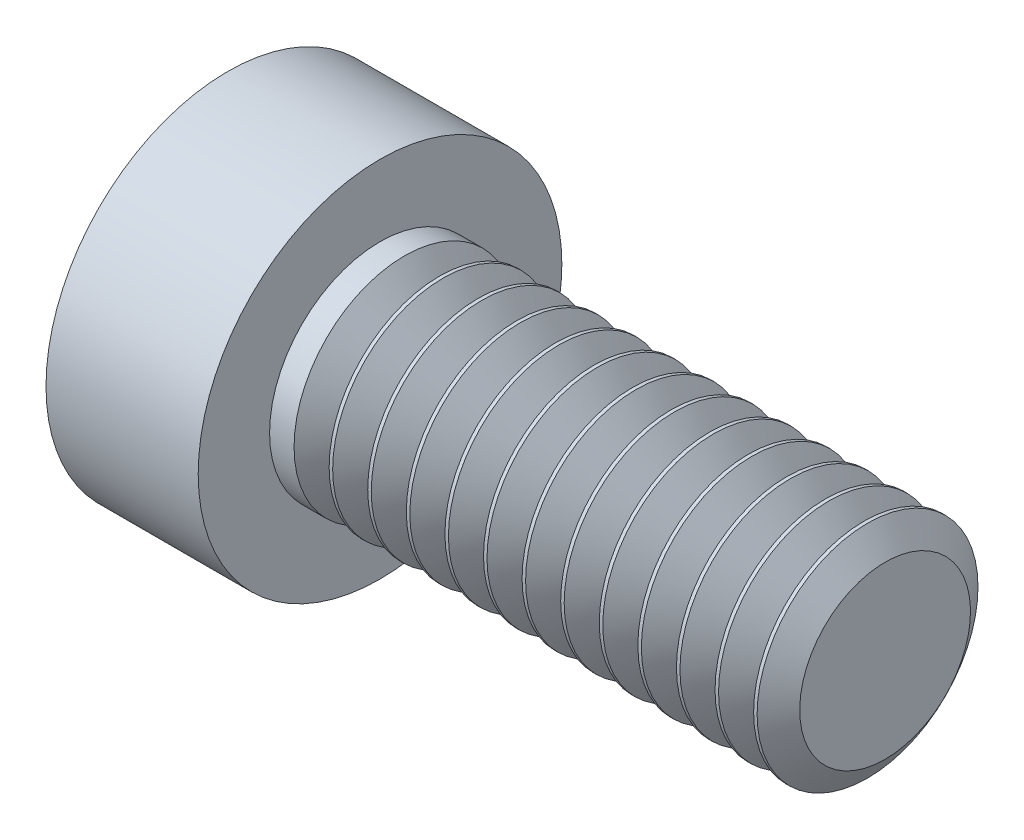
SolidWorks part; units mm, degrees
ref_plane "Plane1" through (0, 0, 0) normal (0, 0, 1) x (1, 0, 0)
ref_plane "Plane2" through (0, 0, 0) normal (0, 1, 0) x (1, 0, 0)
ref_plane "Plane3" through (0, 0, 0) normal (1, 0, 0) x (0, 0, -1)
sketch "BodySke" plane through (0, 0, 0) normal (0, 0, 1) x (1, 0, 0)
  line L0 (3.9624, 2.0828) -> (3.9624, 3.429)
  line L1 (3.9624, 3.429) -> (1.0922, 3.429)
  line L2 (-25.4, 0) -> (127, 0) construction
  line L3 (13.4874, 0) -> (0, 0)
  line L4 (3.9624, 2.0828) -> (13.4874, 2.0828)
  line L5 (13.4874, 2.0828) -> (13.4874, 0)
  line L6 (3.9624, -3.429) -> (1.0922, -3.429) construction
  line L7 (3.9624, -2.0828) -> (13.4874, -2.0828) construction
  line L8 (4.7549, 1.2192) -> (4.7549, -0.4698) construction
  line L9 (3.9624, 1.2192) -> (3.9624, -0.4698) construction
  arc A0 (0, 0) -> (1.0922, 3.429) centre (5.9288, 0) cw
  dimension "Diameter" = 4.1656
  dimension "Head_dia" = 6.858
  dimension "Head_ht" = 3.9624
  dimension "Length" = 9.525
  dimension "Head_side_ht" = 2.8702
  dimension "Thread_nom" = 9.525
  dimension "Advance" = 0.7925
revolve "Base-Revolve" add sketch "BodySke" angle 360 about L2
cosmetic thread "ThreadCosmetic" [suppressed] parameters "Thread_length"=8.7325, "Thread_minor"=3.2207
sketch "Sketch2" plane through (0, 0, 0) normal (1, 0, 0) x (0, 0, -1)
  line L0 (-3.429, -0.6858) -> (-3.429, 0.6858)
  line L1 (-3.429, 0.6858) -> (3.429, 0.6858)
  line L2 (3.429, 0.6858) -> (3.429, -0.6858)
  line L3 (3.429, -0.6858) -> (-3.429, -0.6858)
  dimension "D1" = 6.858
  dimension "D2" = 3.429
  dimension "D3" = 0.6858
  dimension "Slot_width" = 1.3716
extrude "Slot" [suppressed] cut sketch "Sketch2" along normal blind 1.8034
sketch "Sketch3" plane through (0, 0, 0) normal (1, 0, 0) x (0, 0, -1)
  line L0 (0.4953, -2.5654) -> (-0.4953, -2.5654)
  line L1 (0.4953, -2.5654) -> (0.4953, 2.5654)
  line L2 (-0.4953, 2.5654) -> (0.4953, 2.5654)
  line L3 (-0.4953, 2.5654) -> (-0.4953, -2.5654)
  dimension "Cross_width" = 0.9906
  dimension "D1" = 0.4953
  dimension "Cross_dia" = 5.1308
  dimension "D2" = 2.5654
ref_plane "Plane4" through (2.9972, 0, 0) normal (1, 0, 0) x (0, 0, -1)
sketch "Sketch4" plane through (2.9972, 0, 0) normal (1, 0, 0) x (0, 0, -1)
  line L0 (0.2477, -0.2476) -> (-0.2476, -0.2477)
  line L1 (0.2477, -0.2476) -> (0.2477, 0.2476)
  line L2 (-0.2476, 0.2476) -> (0.2477, 0.2476)
  line L3 (-0.2476, 0.2476) -> (-0.2476, -0.2477)
  dimension "D1" = 0.4953
  dimension "D2" = 0.2476
  dimension "D3" = 0.4953
  dimension "D4" = 0.2476
loft "Cross" cut profiles "Sketch3", "Sketch4"
pattern_circular "CirPattern1" count 2 every 90 about axis through (0, 0, 0) along (1, 0, 0) of "Cross"
sketch "Sketch5" plane through (0, 0, 0) normal (0, 1, 0) x (1, 0, 0)
  line L4 (-25.4, 0) -> (127, 0) construction
  line L5 (3.9624, -6.312) -> (3.9624, 6.3337) construction
  circle A0 centre (2.8702, 0) radius 0.5842
  dimension "Drilled_hole_dia" = 1.1684
  dimension "D1" = 3.9624
  dimension "Drilled_hole_loc" = 1.0922
extrude "Hole" [suppressed] cut sketch "Sketch5" against normal through all and the other way through all
sketch "ThdSchSke" plane through (0, 0, 0) normal (0, 0, 1) x (1, 0, 0)
  line L0 (4.7549, -1.6104) -> (4.4241, -2.0828)
  line L1 (4.7549, -1.6104) -> (5.0857, -2.0828)
  line L2 (5.0857, -2.0828) -> (5.0857, -2.6035)
  line L3 (-3.175, 0) -> (5.1513, 0) construction
  line L5 (5.0857, -2.6035) -> (4.4241, -2.6035)
  line L6 (4.4241, -2.6035) -> (4.4241, -2.0828)
  dimension "Diameter" = 4.1656
  dimension "SideAngle" = 55
  dimension "VeeAngle" = 70
  dimension "Thread_minor" = 3.2207
  dimension "Overcut" = 5.207
  dimension "Start" = 4.7549
revolve "ThreadSchematic" cut sketch "ThdSchSke" angle 360 about L3
pattern_linear "ThdSchPat" count 13 spacing 0.7277 along (1, 0, 0) of "ThreadSchematic"
equation "\"D1@Sketch3\" = \"Cross_width@Sketch3\" / 2"
equation "\"D2@Sketch3\" = \"Cross_dia@Sketch3\" / 2"
equation "\"D1@Sketch4\" = \"Cross_width@Sketch3\"*.5"
equation "\"D2@Sketch4\" = \"D1@Sketch4\" / 2"
equation "\"D3@Sketch4\" = \"D1@Sketch4\""
equation "\"D4@Sketch4\" = \"D2@Sketch4\""
equation "\"D1@Sketch2\" = \"Head_dia@BodySke\""
equation "\"D2@Sketch2\" = \"D1@Sketch2\" / 2"
equation "\"D3@Sketch2\" = \"Slot_width@Sketch2\" / 2"
equation "\"D1@Sketch5\" = \"Head_ht@BodySke\""
equation "\"Thread_length@ThreadCosmetic\" = ((sgn( (\"Length@BodySke\" - \"Advance@BodySke\" ) - \"Thread_nom@BodySke\" )-1)*( (\"Length@BodySke\" - \"Advance@BodySke\" ) - \"Thread_nom@BodySke\" ))/-2+ \"Thread_nom@BodySke\""
equation "\"Thread_minor@ThdSchSke\" = \"Thread_minor@ThreadCosmetic\""
equation "\"Diameter@ThdSchSke\" = \"Diameter@BodySke\""
equation "\"Overcut@ThdSchSke\" = \"Diameter@BodySke\" * 1.25"
equation "\"Start@ThdSchSke\" = \"Head_ht@BodySke\" + \"Length@BodySke\" - \"Thread_length@ThreadCosmetic\"  '---Non-countersunk---"
equation "\"Num_threads@ThdSchPat\" = int( \"Thread_length@ThreadCosmetic\" / \"Advance@BodySke\" + 0.999 )  + 1"
equation "\"Advance@ThdSchPat\" = \"Thread_length@ThreadCosmetic\" /  (\"Num_threads@ThdSchPat\" - 1) 'relax it"
